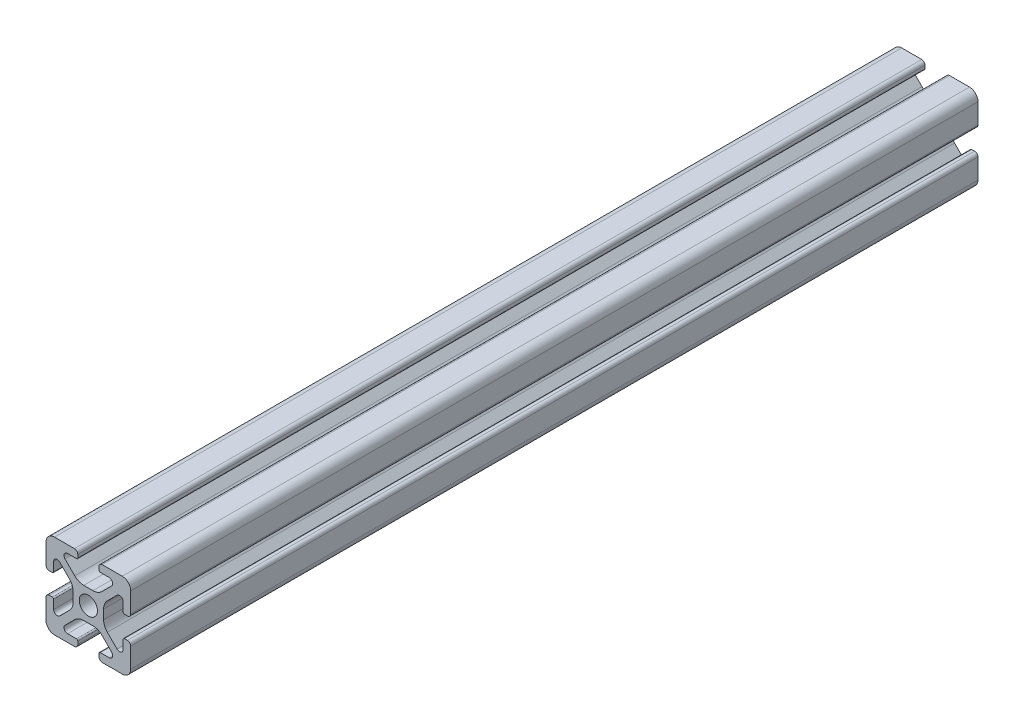
SolidWorks part; units mm, degrees
ref_plane "Front Plane" through (0, 0, 0) normal (0, 0, 1) x (1, 0, 0)
ref_plane "Top Plane" through (0, 0, 0) normal (0, 1, 0) x (1, 0, 0)
ref_plane "Right Plane" through (0, 0, 0) normal (1, 0, 0) x (0, 0, -1)
sketch "Sketch1" plane through (0, 0, 0) normal (0, 0, 1) x (1, 0, 0)
  line L0 (0, 10) -> (0, -10) construction
  line L1 (10, 0) -> (-10, 0) construction
  line L2 (-2.5, 10) -> (2.5, 10) construction
  line L3 (-5.75, 8.2) -> (5.75, 8.2) construction
  circle A0 centre (0, 0) radius 2.15 construction
  point P4 (0, 0)
  point P8 (0, 0)
  point P10 (0, 3.6)
  point P14 (0, 10)
  point P17 (0, 8.2)
  dimension "Thru Hole" = 4.3
  dimension "Height" = 20
  dimension "T Slot Depth" = 6.4
  dimension "T Slot Top Width" = 5
  dimension "T Slot Max Width" = 11.5
  dimension "Wall" = 1.8
sketch "Sketch2" plane through (0, 0, 0) normal (1, 0, 0) x (0, 0, -1)
  line L0 (100, 0) -> (-100, 0) construction
  point P4 (0, 0)
  dimension "D1" = 200
sketch "Sketch3" plane through (0, 0, 0) normal (0, 0, 1) x (1, 0, 0)
  line L0 (3.2874, 10) -> (8, 10)
  line L1 (10, 8) -> (10, -8) construction
  line L2 (8, -10) -> (-8, -10) construction
  line L3 (-10, 10) -> (10, -10) construction
  line L4 (2.5, 9.2126) -> (2.5, 8.5048)
  line L5 (-5.75, 8.2) -> (5.75, 8.2) construction
  line L6 (2.8048, 8.2) -> (4.9118, 8.2)
  line L7 (5.5045, 6.7691) -> (3.2141, 4.4787)
  line L8 (1.0928, 3.6) -> (-1.0928, 3.6)
  line L9 (0, 10) -> (0, -10) construction
  line L10 (5.75, 8.2) -> (5.75, 0) construction
  line L11 (10, 0) -> (-10, 0) construction
  line L12 (0, 0) -> (0, 10) construction
  line L13 (-2.5, 9.2126) -> (-2.5, 8.5048)
  line L14 (-5.5045, 6.7691) -> (-3.2141, 4.4787)
  line L15 (-2.8048, 8.2) -> (-4.9118, 8.2)
  line L16 (-3.2874, 10) -> (-8, 10)
  line L17 (0, 0) -> (-10, 0) construction
  line L18 (-10, 3.2874) -> (-10, 8)
  line L19 (-8.2, 2.8048) -> (-8.2, 4.9118)
  line L20 (-6.7691, 5.5045) -> (-4.4787, 3.2141)
  line L21 (-9.2126, 2.5) -> (-8.5048, 2.5)
  line L22 (-3.6, -1.0928) -> (-3.6, 1.0928)
  line L23 (-6.7691, -5.5045) -> (-4.4787, -3.2141)
  line L24 (-8.2, -2.8048) -> (-8.2, -4.9118)
  line L25 (-9.2126, -2.5) -> (-8.5048, -2.5)
  line L26 (-10, -3.2874) -> (-10, -8)
  line L27 (9.2126, -2.5) -> (8.5048, -2.5)
  line L28 (8.2, -2.8048) -> (8.2, -4.9118)
  line L29 (6.7691, -5.5045) -> (4.4787, -3.2141)
  line L30 (3.6, -1.0928) -> (3.6, 1.0928)
  line L31 (9.2126, 2.5) -> (8.5048, 2.5)
  line L32 (6.7691, 5.5045) -> (4.4787, 3.2141)
  line L33 (8.2, 2.8048) -> (8.2, 4.9118)
  line L34 (10, 8) -> (10, 3.2874)
  line L35 (10, -3.2874) -> (10, -8)
  line L36 (3.2874, -10) -> (8, -10)
  line L37 (-3.2874, -10) -> (-8, -10)
  line L38 (-6.7691, -5.5045) -> (-4.4787, -3.2141)
  line L39 (-2.8048, -8.2) -> (-4.9118, -8.2)
  line L40 (-5.5045, -6.7691) -> (-3.2141, -4.4787)
  line L41 (-2.5, -9.2126) -> (-2.5, -8.5048)
  line L42 (1.0928, -3.6) -> (-1.0928, -3.6)
  line L43 (5.5045, -6.7691) -> (3.2141, -4.4787)
  line L44 (2.8048, -8.2) -> (4.9118, -8.2)
  line L45 (2.5, -9.2126) -> (2.5, -8.5048)
  arc A0 (4.9118, 8.2) -> (5.5045, 6.7691) centre (4.9118, 7.3618) cw
  arc A1 (3.2141, 4.4787) -> (1.0928, 3.6) centre (1.0928, 6.6) cw
  circle A2 centre (0, 0) radius 2.15 construction
  circle A3 centre (0, 0) radius 2.15
  arc A4 (3.2874, 10) -> (2.5, 9.2126) centre (3.2874, 9.2126) ccw
  arc A5 (2.5, 8.5048) -> (2.8048, 8.2) centre (2.8048, 8.5048) ccw
  arc A6 (-3.2874, 10) -> (-2.5, 9.2126) centre (-3.2874, 9.2126) cw
  arc A7 (-4.9118, 8.2) -> (-5.5045, 6.7691) centre (-4.9118, 7.3618) ccw
  arc A8 (-3.2141, 4.4787) -> (-1.0928, 3.6) centre (-1.0928, 6.6) ccw
  arc A9 (-2.5, 8.5048) -> (-2.8048, 8.2) centre (-2.8048, 8.5048) cw
  arc A10 (-8.5048, 2.5) -> (-8.2, 2.8048) centre (-8.5048, 2.8048) ccw
  arc A11 (-4.4787, 3.2141) -> (-3.6, 1.0928) centre (-6.6, 1.0928) cw
  arc A12 (-8.2, 4.9118) -> (-6.7691, 5.5045) centre (-7.3618, 4.9118) cw
  arc A13 (-10, 3.2874) -> (-9.2126, 2.5) centre (-9.2126, 3.2874) ccw
  arc A14 (-8.5048, -2.5) -> (-8.2, -2.8048) centre (-8.5048, -2.8048) cw
  arc A15 (-10, -3.2874) -> (-9.2126, -2.5) centre (-9.2126, -3.2874) cw
  arc A16 (-4.4787, -3.2141) -> (-3.6, -1.0928) centre (-6.6, -1.0928) ccw
  arc A17 (-8.2, -4.9118) -> (-6.7691, -5.5045) centre (-7.3618, -4.9118) ccw
  arc A26 (-8, -10) -> (-10, -8) centre (-8, -8) cw
  arc A27 (-8, 10) -> (-10, 8) centre (-8, 8) ccw
  arc A28 (8, 10) -> (10, 8) centre (8, 8) cw
  arc A29 (10, -8) -> (8, -10) centre (8, -8) cw
  arc A30 (8.2, -4.9118) -> (6.7691, -5.5045) centre (7.3618, -4.9118) cw
  arc A31 (4.4787, -3.2141) -> (3.6, -1.0928) centre (6.6, -1.0928) cw
  arc A32 (10, -3.2874) -> (9.2126, -2.5) centre (9.2126, -3.2874) ccw
  arc A33 (8.5048, -2.5) -> (8.2, -2.8048) centre (8.5048, -2.8048) ccw
  arc A34 (10, 3.2874) -> (9.2126, 2.5) centre (9.2126, 3.2874) cw
  arc A35 (8.2, 4.9118) -> (6.7691, 5.5045) centre (7.3618, 4.9118) ccw
  arc A36 (4.4787, 3.2141) -> (3.6, 1.0928) centre (6.6, 1.0928) ccw
  arc A37 (8.5048, 2.5) -> (8.2, 2.8048) centre (8.5048, 2.8048) cw
  arc A38 (-2.5, -8.5048) -> (-2.8048, -8.2) centre (-2.8048, -8.5048) ccw
  arc A39 (-3.2141, -4.4787) -> (-1.0928, -3.6) centre (-1.0928, -6.6) cw
  arc A40 (-4.9118, -8.2) -> (-5.5045, -6.7691) centre (-4.9118, -7.3618) cw
  arc A41 (-3.2874, -10) -> (-2.5, -9.2126) centre (-3.2874, -9.2126) ccw
  arc A42 (2.5, -8.5048) -> (2.8048, -8.2) centre (2.8048, -8.5048) cw
  arc A43 (3.2874, -10) -> (2.5, -9.2126) centre (3.2874, -9.2126) cw
  arc A44 (3.2141, -4.4787) -> (1.0928, -3.6) centre (1.0928, -6.6) ccw
  arc A45 (4.9118, -8.2) -> (5.5045, -6.7691) centre (4.9118, -7.3618) ccw
  point P36 (2.5, 10)
  point P39 (2.5, 8.2)
  point P49 (0, 3.6)
  point P77 (-3.6, 0)
  point P78 (-8.2, -2.5)
  point P79 (-10, -2.5)
  point P104 (-10, -10)
  point P110 (10, 10)
  point P114 (10, -2.5)
  point P115 (8.2, -2.5)
  point P116 (3.6, 0)
  point P141 (0, -3.6)
  dimension "D1" = 3
  dimension "D2" = 0.8382
  dimension "D4" = 0.7874
  dimension "D5" = 0.3048
  dimension "D6" = 2
  dimension "D3" = 45
extrude "Boss-Extrude1" add sketch "Sketch3" along normal up to vertex (100 mm away) and the other way up to vertex (100 mm away) contours A45 L44 A42 L45 A43 L36 A29 L35 A32 L27 A33 L28 A30 L29 A31 L30 A36 L32 A35 L33 A37 L31 A34 L34 A28 L0 A4 L4 A5 L6 A0 L7 A1 L8 A8 L14 A7 L15 A9 L13 A6 L16 A27 L18 A13 L21 A10 L19 A12 L20 A11 up to point (0, 0, 100) other way up to point (0, 0, -100)
